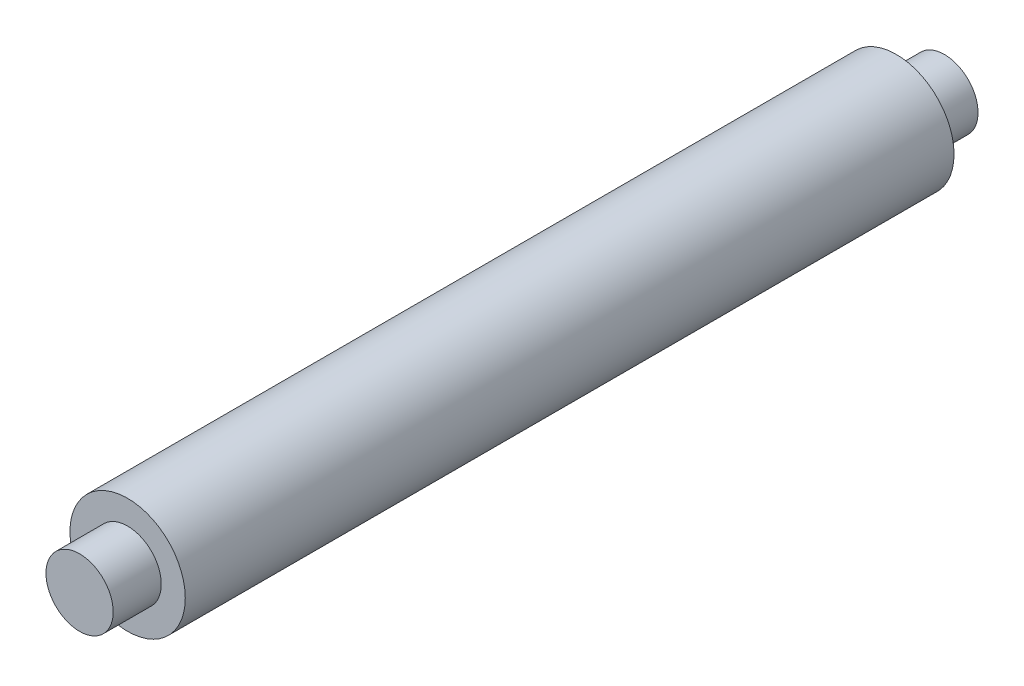
SolidWorks part; units mm, degrees
material "Pino"
ref_plane "Alzado" through (0, 0, 0) normal (0, 0, 1) x (1, 0, 0)
ref_plane "Planta" through (0, 0, 0) normal (0, 1, 0) x (1, 0, 0)
ref_plane "Vista lateral" through (0, 0, 0) normal (1, 0, 0) x (0, 0, -1)
sketch "Croquis1" plane through (0, 0, 0) normal (0, 0, 1) x (1, 0, 0)
  circle A0 centre (0, 0) radius 24
  dimension "D1" = 48
extrude "Saliente-Extruir1" add sketch "Croquis1" along normal blind 320
sketch "Croquis2" plane through (0, 0, 0) normal (0, 0, -1) x (-1, 0, 0)
  circle A0 centre (0, 0) radius 14
  dimension "D1" = 28
extrude "Saliente-Extruir2" add sketch "Croquis2" along normal blind 20
sketch "Croquis3" plane through (0, 0, 320) normal (0, 0, 1) x (1, 0, 0)
  circle A0 centre (0, 0) radius 14
  dimension "D1" = 28
extrude "Saliente-Extruir3" add sketch "Croquis3" along normal blind 20
